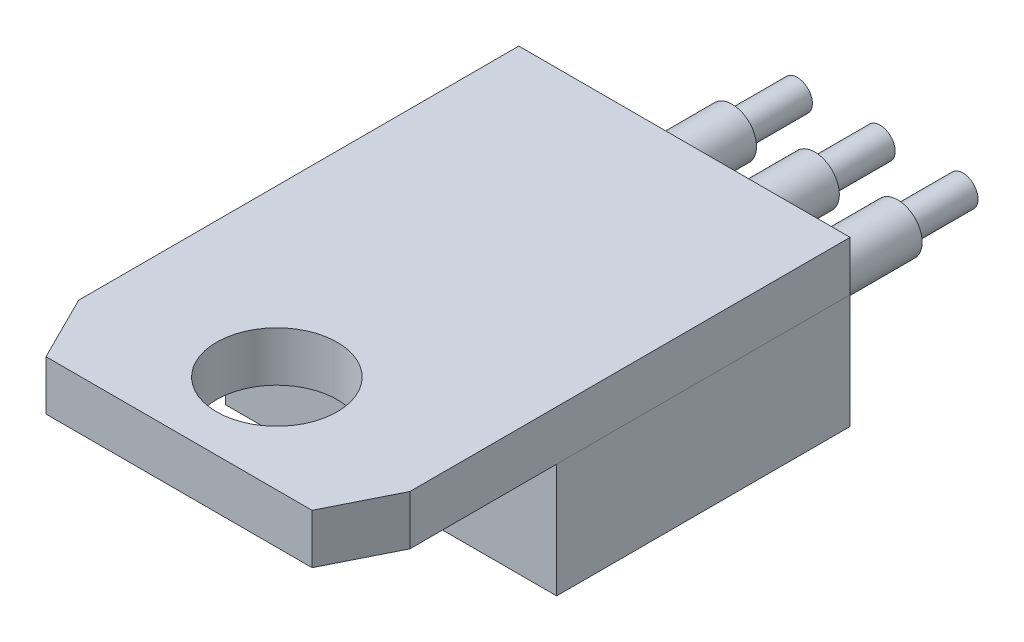
SolidWorks part; units mm, degrees
ref_plane "Front" through (0, 0, 0) normal (0, 0, 1) x (1, 0, 0)
ref_plane "Top" through (0, 0, 0) normal (0, 1, 0) x (1, 0, 0)
ref_plane "Right" through (0, 0, 0) normal (1, 0, 0) x (0, 0, -1)
ref_plane "Plane1" through (0, 165.5904, 0) normal (0, -1, 0) x (1, 0, 0)
sketch "Sketch1" plane through (0, 165.5904, 0) normal (0, -1, 0) x (1, 0, 0)
  line L0 (-4.08, 15.5) -> (-5.08, 13.5)
  line L1 (-5.08, 13.5) -> (-5.08, 0)
  line L2 (-5.08, 0) -> (5.08, 0)
  line L3 (5.08, 0) -> (5.08, 13.5)
  line L4 (5.08, 13.5) -> (4.08, 15.5)
  line L5 (4.08, 15.5) -> (-4.08, 15.5)
  line L6 (0, 12.5) -> (0, 0) construction
  circle A0 centre (0, 12.5) radius 1.85
  dimension "D3" = 3.7
  dimension "D1" = 15.5
  dimension "D2" = 10.16
  dimension "D4" = 12.5
  dimension "D5" = 2
  dimension "D6" = 1
extrude "Boss-Extrude1" add sketch "Sketch1" against normal blind 1.524
sketch "Sketch2" plane through (0, 165.5904, 0) normal (0, -1, 0) x (1, 0, 0)
  line L0 (5.08, 9) -> (-5.08, 9)
  line L1 (-5.08, 9) -> (-5.08, 0)
  line L2 (-5.08, 0) -> (5.08, 0)
  line L3 (5.08, 0) -> (5.08, 9)
  line L4 (5.08, 0) -> (5.08, 13.5) construction
  line L5 (-5.08, 13.5) -> (-5.08, 0) construction
  line L6 (-5.08, 0) -> (5.08, 0) construction
  dimension "D1" = 9
extrude "Boss-Extrude2" add sketch "Sketch2" along normal blind 3.5
sketch "Sketch3" plane through (0, 0, 0) normal (0, 0, -1) x (-1, 0, 0)
  line L1 (5.08, 167.1144) -> (5.08, 162.0904) construction
  line L2 (0, 167.1144) -> (0, 162.0904) construction
  line L3 (5.08, 167.1144) -> (-5.08, 167.1144) construction
  line L4 (5.08, 162.0904) -> (-5.08, 162.0904) construction
  circle A0 centre (2.54, 164.0904) radius 0.75
  circle A1 centre (0, 164.0904) radius 0.75
  circle A2 centre (-2.54, 164.0904) radius 0.75
  dimension "D2" = 1.5
  dimension "D1" = 2
  dimension "D3" = 2.54
extrude "Boss-Extrude3" add sketch "Sketch3" along normal blind 4
sketch "Sketch6" plane through (0, 0, -4) normal (0, 0, -1) x (-1, 0, 0)
  circle A0 centre (2.54, 164.0904) radius 0.4636
  circle A1 centre (2.54, 164.0904) radius 0.75 construction
  circle A2 centre (0, 164.0904) radius 0.4636
  circle A3 centre (-2.54, 164.0904) radius 0.4636
  dimension "D1" = 0.9271
extrude "Boss-Extrude6" add sketch "Sketch6" along normal blind 2
sketch "Sketch7" plane through (-5.08, 0, 0) normal (-1, 0, 0) x (0, 0, 1)
  line L0 (9, 165.5904) -> (0, 165.5904)
  line L1 (0, 167.1144) -> (0, 162.0904) construction
split line "Split Line1"
